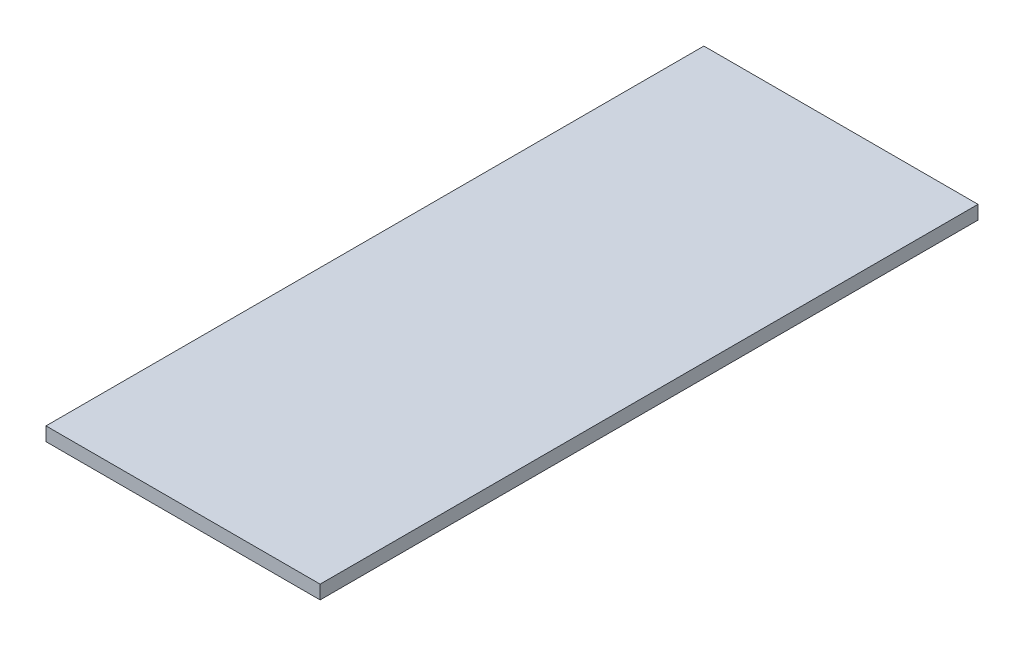
SolidWorks part; units mm, degrees
material "Mahogany"
ref_plane "Front Plane" through (0, 0, 0) normal (0, 0, 1) x (1, 0, 0)
ref_plane "Top Plane" through (0, 0, 0) normal (0, 1, 0) x (1, 0, 0)
ref_plane "Right Plane" through (0, 0, 0) normal (1, 0, 0) x (0, 0, -1)
sketch "Sketch1" plane through (0, 0, 0) normal (0, 1, 0) x (1, 0, 0)
  line L1 (0, 0) -> (254, 0)
  line L2 (0, 0) -> (0, 609.6)
  line L3 (0, 609.6) -> (254, 609.6)
  line L4 (254, 0) -> (254, 609.6)
  dimension "D1" = 254
  dimension "D2" = 609.6
extrude "Boss-Extrude1" add sketch "Sketch1" along normal blind 12.7 contours L2 L1 L4 L3
